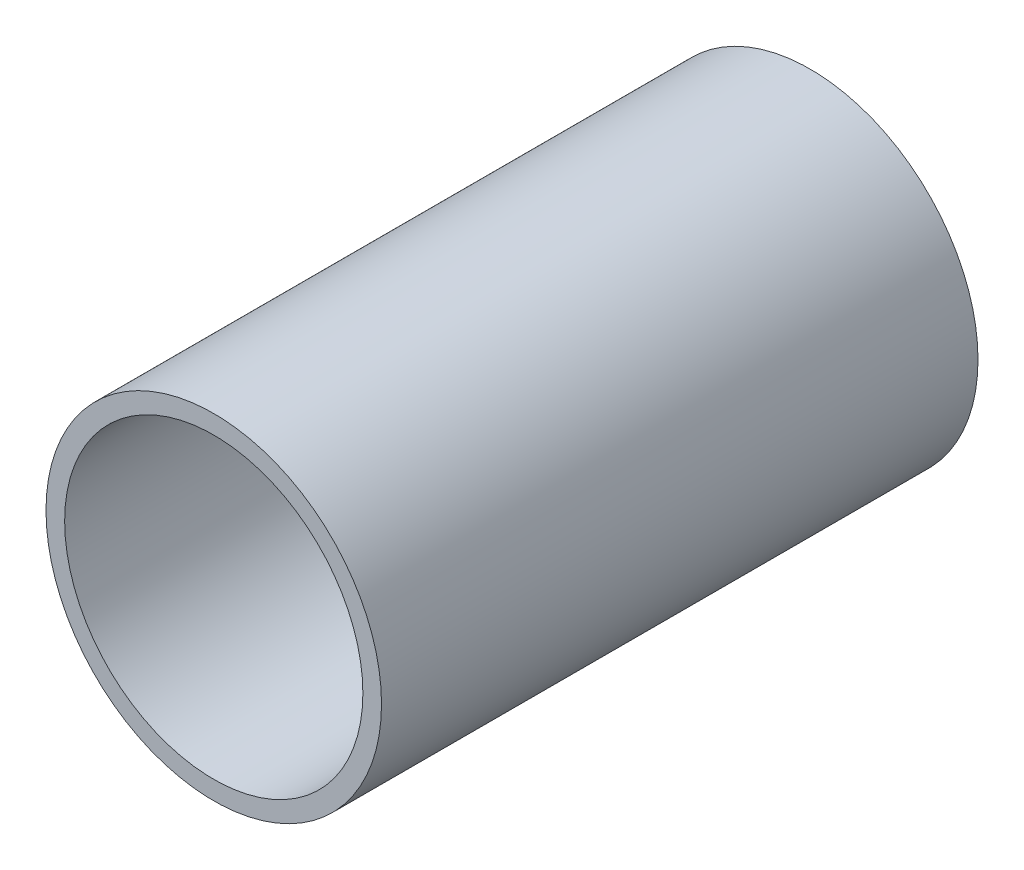
SolidWorks part; units mm, degrees
material "ABS PC"
ref_plane "Front Plane" through (0, 0, 0) normal (0, 0, 1) x (1, 0, 0)
ref_plane "Top Plane" through (0, 0, 0) normal (0, 1, 0) x (1, 0, 0)
ref_plane "Right Plane" through (0, 0, 0) normal (1, 0, 0) x (0, 0, -1)
sketch "Sketch1" plane through (0, 0, 0) normal (0, 0, 1) x (1, 0, 0)
  circle A0 centre (0, 0) radius 57.15
  circle A1 centre (0, 0) radius 50.8
  dimension "D1" = 114.3
  dimension "D2" = 101.6
extrude "Boss-Extrude1" add sketch "Sketch1" along normal mid plane 203.2
